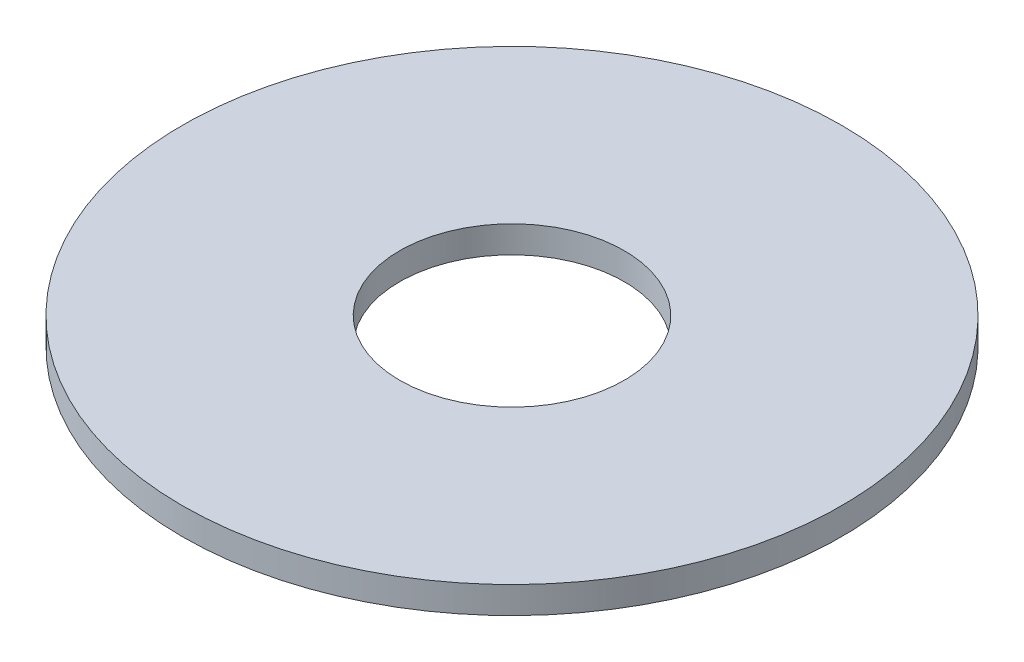
SolidWorks part; units mm, degrees
material "Сосна"
ref_plane "Спереди" through (0, 0, 0) normal (0, 0, 1) x (1, 0, 0)
ref_plane "Сверху" through (0, 0, 0) normal (0, 1, 0) x (1, 0, 0)
ref_plane "Справа" through (0, 0, 0) normal (1, 0, 0) x (0, 0, -1)
sketch "Эскиз1" plane through (0, 0, 0) normal (0, 1, 0) x (1, 0, 0)
  circle A0 centre (0, 0) radius 49
  circle A1 centre (0, 0) radius 16.7
extrude "Бобышка-Вытянуть1" add sketch "Эскиз1" along normal blind 4
